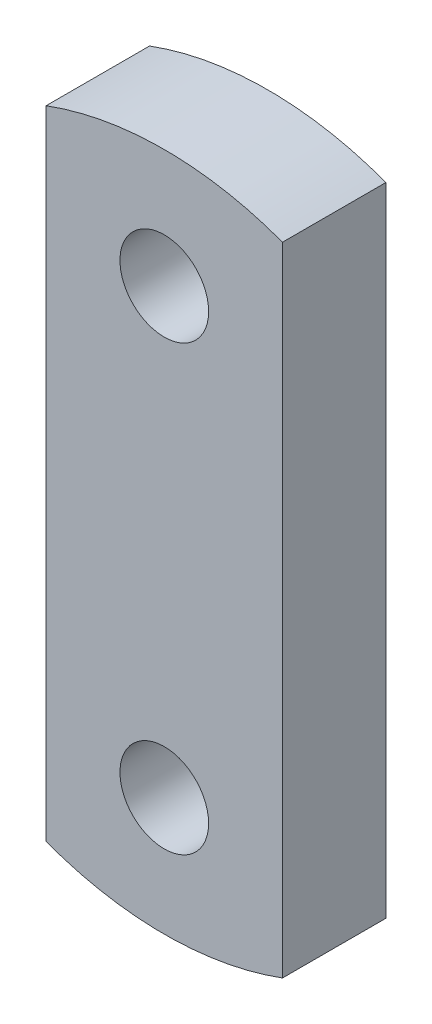
SolidWorks part; units mm, degrees
ref_plane "Front Plane" through (0, 0, 0) normal (0, 0, 1) x (1, 0, 0)
ref_plane "Top Plane" through (0, 0, 0) normal (0, 1, 0) x (1, 0, 0)
ref_plane "Right Plane" through (0, 0, 0) normal (1, 0, 0) x (0, 0, -1)
sketch "Sketch1" plane through (0, 0, 0) normal (0, 0, 1) x (1, 0, 0)
  line L0 (0, 0) -> (0, 140.9016) construction
  line L1 (-40, 107.8193) -> (-40, -107.8193)
  line L2 (40, 107.8193) -> (40, -107.8193)
  arc A0 (40, 107.8193) -> (-40, 107.8193) centre (0, 0) ccw
  arc A1 (-40, -107.8193) -> (40, -107.8193) centre (0, 0) ccw
  circle A2 centre (0, -75) radius 15
  circle A3 centre (0, 75) radius 15
  dimension "D1" = 230
  dimension "D5" = 30
  dimension "D6" = 30
  dimension "D2" = 40
  dimension "D3" = 75
  dimension "D4" = 75
extrude "Boss-Extrude1" add sketch "Sketch1" along normal blind 35
